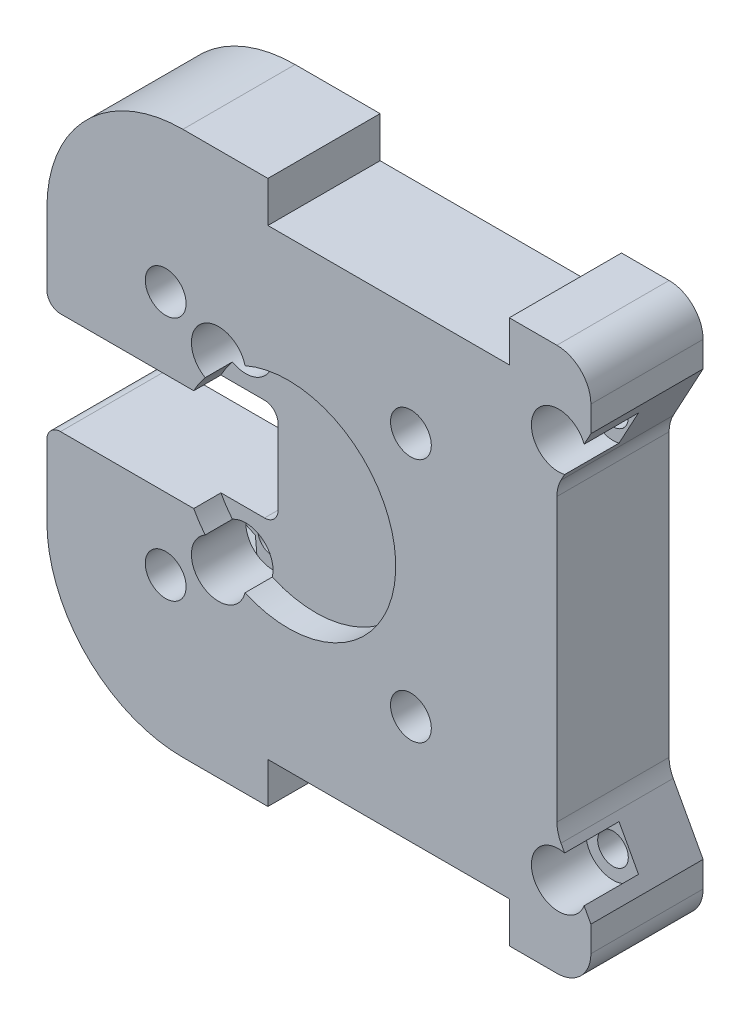
SolidWorks part; units mm, degrees
material "PEI"
ref_plane "前视基准面" through (0, 0, 0) normal (0, 0, 1) x (1, 0, 0)
ref_plane "上视基准面" through (0, 0, 0) normal (0, 1, 0) x (1, 0, 0)
ref_plane "右视基准面" through (0, 0, 0) normal (1, 0, 0) x (0, 0, -1)
sketch "草图1" plane through (0, 0, 0) normal (0, 0, 1) x (1, 0, 0)
  line L1 (-36.24, 26.4094) -> (43.76, 26.4094)
  line L2 (-36.24, 26.4094) -> (-36.24, -53.5906)
  line L3 (-36.24, -53.5906) -> (43.76, -53.5906)
  line L4 (43.76, 26.4094) -> (43.76, -53.5906)
  dimension "D1" = 80
  dimension "D2" = 80
extrude "凸台-拉伸1" add sketch "草图1" along normal blind 16.5
fillet "圆角1" radius 20 2 edges at (-36.24, -53.5906, 8.25) (-36.24, 26.4094, 8.25)
fillet "圆角2" radius 5 2 edges at (43.76, -53.5906, 8.25) (43.76, 26.4094, 8.25)
sketch "草图2" plane through (0, 0, 0) normal (0, 0, -1) x (-1, 0, 0)
  line L0 (36.24, 6.4094) -> (36.24, -33.5906) construction
  line L1 (36.24, -6.0906) -> (6.24, -6.0906)
  line L2 (36.24, -6.0906) -> (36.24, -21.0906)
  line L3 (36.24, -21.0906) -> (6.24, -21.0906)
  line L4 (6.24, -6.0906) -> (6.24, -21.0906)
  line L5 (-38.76, 26.4094) -> (16.24, 26.4094) construction
  line L6 (16.24, -53.5906) -> (-38.76, -53.5906) construction
  dimension "D1" = 32.5
  dimension "D2" = 32.5
  dimension "D3" = 30
extrude "切除-拉伸1" cut sketch "草图2" against normal through all
fillet "圆角3" radius 2 4 edges at (-6.24, -6.0906, 8.25) (-6.24, -21.0906, 8.25) (-36.24, -21.0906, 8.25) (-36.24, -6.0906, 8.25)
sketch "草图3" plane through (0, 0, 16.5) normal (0, 0, 1) x (1, 0, 0)
  line L0 (38.76, 26.4094) -> (-16.24, 26.4094) construction
  line L1 (-3.74, 26.4094) -> (31.76, 26.4094)
  line L2 (-3.74, 26.4094) -> (-3.74, 20.4094)
  line L3 (-3.74, 20.4094) -> (31.76, 20.4094)
  line L4 (31.76, 26.4094) -> (31.76, 20.4094)
  line L5 (-36.24, 6.4094) -> (-36.24, -4.0906) construction
  line L6 (43.76, -48.5906) -> (43.76, 21.4094) construction
  dimension "D1" = 32.5
  dimension "D2" = 12
  dimension "D3" = 6
extrude "切除-拉伸2" cut sketch "草图3" against normal through all
sketch "草图4" plane through (0, 0, 16.5) normal (0, 0, 1) x (1, 0, 0)
  line L0 (-16.24, -53.5906) -> (38.76, -53.5906) construction
  line L1 (-3.74, -47.5906) -> (31.76, -47.5906)
  line L2 (-3.74, -47.5906) -> (-3.74, -53.5906)
  line L3 (-3.74, -53.5906) -> (31.76, -53.5906)
  line L4 (31.76, -47.5906) -> (31.76, -53.5906)
  line L5 (-36.24, -23.0906) -> (-36.24, -33.5906) construction
  line L6 (43.76, -48.5906) -> (43.76, 21.4094) construction
  dimension "D1" = 32.5
  dimension "D2" = 12
  dimension "D3" = 6
extrude "切除-拉伸3" cut sketch "草图4" against normal through all
sketch "草图5" plane through (0, 0, 16.5) normal (0, 0, 1) x (1, 0, 0)
  line L0 (43.76, -48.5906) -> (43.76, 21.4094) construction
  line L1 (43.76, 8.4094) -> (38.76, 8.4094)
  line L2 (43.76, 8.4094) -> (43.76, -35.5906)
  line L3 (43.76, -35.5906) -> (38.76, -35.5906)
  line L4 (38.76, 8.4094) -> (38.76, -35.5906)
  line L5 (38.76, 26.4094) -> (31.76, 26.4094) construction
  dimension "D1" = 18
  dimension "D2" = 18
  dimension "D3" = 5
extrude "切除-拉伸4" cut sketch "草图5" against normal through all
sketch "草图8" plane through (0, 0, 16.5) normal (0, 0, 1) x (1, 0, 0)
  line L0 (43.76, -48.5906) -> (43.76, -35.5906) construction
  line L1 (31.76, -53.5906) -> (38.76, -53.5906) construction
  line L2 (43.76, 8.4094) -> (43.76, 21.4094) construction
  line L4 (38.76, 26.4094) -> (31.76, 26.4094) construction
  line L5 (-16.24, -53.5906) -> (-3.74, -53.5906) construction
  line L6 (-36.24, -23.0906) -> (-36.24, -33.5906) construction
  line L7 (-3.74, 26.4094) -> (-16.24, 26.4094) construction
  line L8 (-36.24, 6.4094) -> (-36.24, -4.0906) construction
  circle A0 centre (39.01, -41.5906) radius 1.9 construction
  circle A1 centre (-10.99, -27.0906) radius 1.9 construction
  circle A2 centre (-10.99, -0.0906) radius 1.9 construction
  circle A3 centre (39.01, 14.4094) radius 1.9 construction
  dimension "D1" = 4.75
  dimension "D2" = 12
  dimension "D3" = 4.75
  dimension "D4" = 12
  dimension "D5" = 26.5
  dimension "D6" = 25.25
  dimension "D7" = 26.5
  dimension "D8" = 25.25
sketch "草图10" plane through (0, 0, 16.5) normal (0, 0, 1) x (1, 0, 0)
  line L0 (-6.24, -13.5906) -> (36.76, -13.5906) construction
  line L1 (-6.24, -8.0906) -> (-6.24, -19.0906) construction
  line L2 (36.76, -31.5906) -> (36.76, 4.4094) construction
  circle A0 centre (-0.74, -13.5906) radius 37.5 construction
  circle A2 centre (-0.74, -13.5906) radius 15.8
  dimension "D1" = 0
  dimension "D2" = 37.5
sketch "草图11" plane through (0, 0, 16.5) normal (0, 0, 1) x (1, 0, 0)
  line L0 (17.2912, 4.4407) -> (-18.7712, -31.6218) construction
  line L1 (17.2912, -31.6218) -> (-18.7712, 4.4407) construction
  line L2 (-26.24, -13.5906) -> (36.76, -13.5906) construction
  line L3 (36.76, -31.5906) -> (36.76, 4.4094) construction
  circle A0 centre (-0.74, -13.5906) radius 25.5 construction
  circle A1 centre (-18.7712, 4.4407) radius 3
  circle A2 centre (17.2912, 4.4407) radius 3
  circle A3 centre (17.2912, -31.6218) radius 3
  circle A4 centre (-18.7712, -31.6218) radius 3
  dimension "D1" = 45
  dimension "D2" = 45
hole_wizard "打孔尺寸(%根据)内六角圆柱头螺钉的类型3" positions "草图17" profile "草图16" counterbore size "M4" standard "GB" end condition up to next
sketch "草图17" plane through (0, 0, 16.5) normal (0, 0, 1) x (1, 0, 0)
  point P0 (-10.99, -0.0906)
  point P3 (-10.99, -27.0906)
  point P6 (39.01, 14.4094)
  point P9 (39.01, -41.5906)
sketch "草图16" plane through (-10.99, -0.0906, 16.5) normal (1, 0, 0) x (0, -1, 0)
  line L0 (0, 0) -> (0, 16.5)
  line L1 (0, 16.5) -> (2.25, 16.5)
  line L3 (2.25, 16.5) -> (2.25, 4.6)
  line L4 (2.25, 4.6) -> (4, 4.6)
  line L5 (4, 4.6) -> (4, 0)
  line L7 (4, 0) -> (0, 0)
  line L11 (0, -6.35) -> (0, 107.95) construction
  dimension "通孔孔直径" = 4.5
  dimension "通孔孔深度" = 16.5
  dimension "柱形沉头孔直径" = 8
  dimension "柱形沉头孔深度" = 4.6
extrude "切除-拉伸5" cut sketch "草图10" against normal blind 4
sketch "草图18" plane through (0, 0, 16.5) normal (0, 0, 1) x (1, 0, 0)
  circle A0 centre (-10.99, -0.0906) radius 4
  circle A1 centre (-10.99, -27.0906) radius 4
  circle A2 centre (39.01, -41.5906) radius 4
  circle A3 centre (39.01, 14.4094) radius 4
extrude "切除-拉伸7" cut sketch "草图18" against normal blind 8
sketch "草图20" plane through (0, 0, 16.5) normal (0, 0, 1) x (1, 0, 0)
  line L0 (38.76, -13.5906) -> (15.06, -13.5906) construction
  line L1 (38.76, 8.4094) -> (38.76, -35.5906) construction
  arc A0 (-7.107, -28.0509) -> (-7.107, 0.8698) centre (-0.74, -13.5906) ccw construction
sketch "草图21" plane through (0, 0, 16.5) normal (0, 0, 1) x (1, 0, 0)
  line L0 (38.76, 8.4094) -> (43.76, 17.6409)
  line L1 (43.76, 8.4094) -> (43.76, 21.4094) construction
  line L3 (38.76, -13.5906) -> (15.06, -13.5906) construction
  line L4 (43.76, 17.6409) -> (43.76, 8.4094)
  line L5 (43.76, 8.4094) -> (38.76, 8.4094)
  line L6 (43.76, -35.5906) -> (38.76, -35.5906)
  line L7 (43.76, -44.822) -> (43.76, -35.5906)
  line L8 (38.76, -35.5906) -> (43.76, -44.822)
extrude "切除-拉伸9" cut sketch "草图21" against normal through all
fillet "圆角4" radius 5 2 edges at (38.76, -35.5906, 8.25) (38.76, 8.4094, 8.25)
extrude "切除-拉伸10" cut sketch "草图11" against normal through all
sketch "草图22" plane through (0, 0, 0) normal (0, 0, -1) x (-1, 0, 0)
  line L0 (-16.7176, 10.7656) -> (-22.4819, 8.0999)
  line L1 (-11.5269, -28.9561) -> (-16.7176, -25.2969)
  line L2 (-16.7176, -25.2969) -> (-22.4819, -27.9626)
  line L3 (-22.4819, -27.9626) -> (-23.0555, -34.2875)
  line L4 (-23.0555, -34.2875) -> (-17.8648, -37.9467)
  line L5 (-17.8648, -37.9467) -> (-12.1005, -35.281)
  line L6 (-12.1005, -35.281) -> (-11.5269, -28.9561)
  line L7 (-23.0555, 1.775) -> (-17.8648, -1.8842)
  line L8 (-11.5269, 7.1064) -> (-16.7176, 10.7656)
  line L9 (-12.1005, 0.7815) -> (-11.5269, 7.1064)
  line L10 (-17.8648, -1.8842) -> (-12.1005, 0.7815)
  line L11 (-22.4819, 8.0999) -> (-23.0555, 1.775)
  line L12 (24.5356, 7.1064) -> (19.3448, 10.7656)
  line L13 (13.5805, 8.0999) -> (13.0069, 1.775)
  line L14 (19.3448, 10.7656) -> (13.5805, 8.0999)
  line L15 (23.962, 0.7815) -> (24.5356, 7.1064)
  line L16 (13.0069, 1.775) -> (18.1976, -1.8842)
  line L17 (18.1976, -1.8842) -> (23.962, 0.7815)
  line L18 (18.1976, -37.9467) -> (23.962, -35.281)
  line L19 (19.3448, -25.2969) -> (13.5805, -27.9626)
  line L20 (23.962, -35.281) -> (24.5356, -28.9561)
  line L21 (24.5356, -28.9561) -> (19.3448, -25.2969)
  line L22 (13.0069, -34.2875) -> (18.1976, -37.9467)
  line L23 (13.5805, -27.9626) -> (13.0069, -34.2875)
  circle A0 centre (-17.2912, -31.6218) radius 5.5 construction
extrude "切除-拉伸11" cut sketch "草图22" against normal blind 8.5
ref_point "点1"
ref_point "点2"
